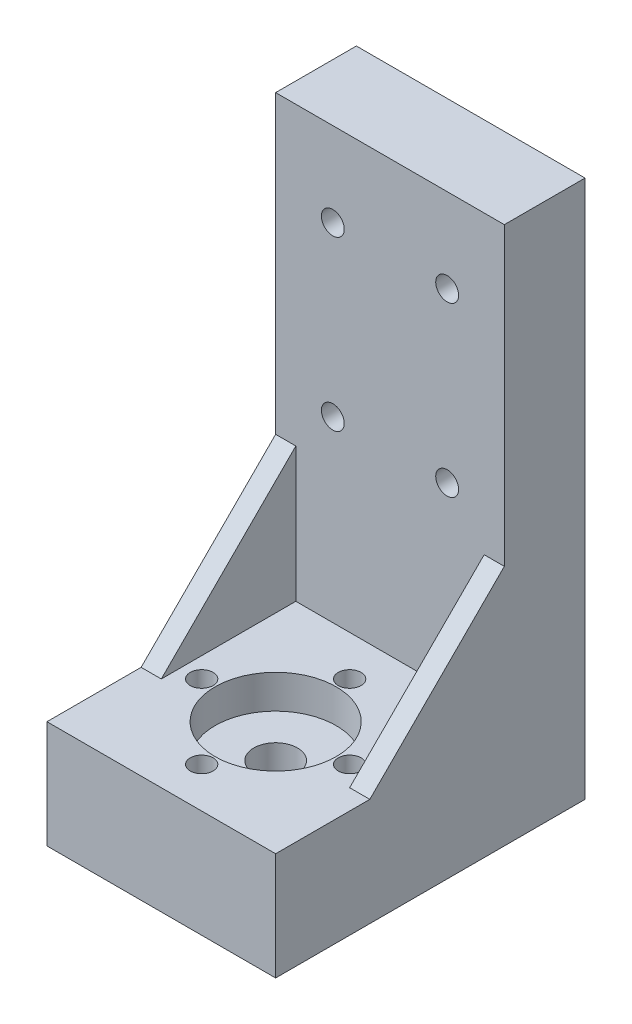
SolidWorks part; units mm, degrees
material "ABS"
ref_plane "Front Plane" through (0, 0, 0) normal (0, 0, 1) x (1, 0, 0)
ref_plane "Top Plane" through (0, 0, 0) normal (0, 1, 0) x (1, 0, 0)
ref_plane "Right Plane" through (0, 0, 0) normal (1, 0, 0) x (0, 0, -1)
sketch "Sketch1" plane through (0, 0, 0) normal (0, 1, 0) x (1, 0, 0)
  line L1 (17, -17) -> (-17, -17)
  line L2 (17, -17) -> (17, 17)
  line L3 (17, 17) -> (-17, 17)
  line L4 (-17, -17) -> (-17, 17)
  line L5 (17, -17) -> (-17, 17) construction
  line L6 (17, 17) -> (-17, -17) construction
  point P0 (0, 0)
  dimension "D1" = 34
  dimension "D2" = 34
extrude "Boss-Extrude1" add sketch "Sketch1" along normal blind 16
sketch "Sketch2" plane through (0, 0, -17) normal (0, 0, -1) x (-1, 0, 0)
  line L1 (-17, 0) -> (17, 0)
  line L2 (-17, 0) -> (-17, 80)
  line L3 (-17, 80) -> (17, 80)
  line L4 (17, 0) -> (17, 80)
  dimension "D1" = 34
  dimension "D2" = 80
extrude "Boss-Extrude2" add sketch "Sketch2" along normal blind 12
sketch "Sketch3" plane through (0, 16, 0) normal (0, 1, 0) x (1, 0, 0)
  line L2 (-17, 17) -> (-17, -17) construction
  line L3 (17, 17) -> (-17, 17) construction
  circle A0 centre (0, 0) radius 3.25
  circle A1 centre (0, 11) radius 1.7
  circle A2 centre (11, 0) radius 1.7
  circle A3 centre (0, -11) radius 1.7
  circle A4 centre (-11, 0) radius 1.7
  point P16 (0, 0)
  dimension "D1" = 6.5
  dimension "D2" = 3.4
  dimension "D3" = 11
  dimension "D4" = 17
  dimension "D6" = 11
  dimension "D7" = 17
  dimension "D5" = 4
extrude "Cut-Extrude2" cut sketch "Sketch3" against normal through all
sketch "Sketch4" plane through (0, 16, 0) normal (0, 1, 0) x (1, 0, 0)
  circle A0 centre (0, 0) radius 9
  dimension "D1" = 18
extrude "Cut-Extrude3" cut sketch "Sketch4" against normal blind 5
sketch "Sketch5" plane through (0, 0, -17) normal (0, 0, 1) x (1, 0, 0)
  line L0 (-17, 16) -> (-17, 80) construction
  line L1 (17, 80) -> (17, 16) construction
  line L2 (-17, 80) -> (17, 80) construction
  circle A0 centre (-8.5, 67.5) radius 1.7
  circle A1 centre (8.5, 67.5) radius 1.7
  circle A2 centre (8.5, 42.5) radius 1.7
  circle A3 centre (-8.5, 42.5) radius 1.7
  dimension "D1" = 3.4
  dimension "D2" = 8.5
  dimension "D3" = 8.5
  dimension "D4" = 12.5
  dimension "D5" = 37.5
extrude "Cut-Extrude4" cut sketch "Sketch5" against normal through all
sketch "Sketch6" plane through (17, 0, 0) normal (1, 0, 0) x (0, 0, -1)
  line L0 (17, 16) -> (-3, 16)
  line L1 (-17, 16) -> (17, 16) construction
  line L2 (17, 16) -> (17, 36)
  line L3 (17, 80) -> (17, 16) construction
  line L4 (17, 36) -> (-3, 16)
  dimension "D1" = 20
  dimension "D2" = 20
extrude "Boss-Extrude3" add sketch "Sketch6" against normal blind 3
sketch "Sketch7" plane through (-17, 0, 0) normal (-1, 0, 0) x (0, 0, 1)
  line L0 (-17, 16) -> (-17, 36)
  line L1 (-17, 16) -> (-17, 80) construction
  line L2 (-17, 16) -> (-17, 36) construction
  line L3 (-17, 16) -> (3, 16)
  line L6 (3, 16) -> (-17, 36)
  line L7 (-17, 36) -> (3, 16) construction
  dimension "D1" = 20
extrude "Boss-Extrude4" add sketch "Sketch7" against normal blind 3
equation "\"Feature 1 Length\"= 34mm"
equation "\"Mount Width\"= 34mm"
equation "\"Feature 1 thickness\"= 16mm"
equation "\"feature 2 height\"= 80mm"
equation "\"Feature 2 thickness\"= 12mm"
equation "\"D2@Sketch1\"=\"Feature 1 Length\""
equation "\"D1@Sketch1\"=\"Mount Width\""
equation "\"D1@Boss-Extrude1\"=\"Feature 1 thickness\""
equation "\"D2@Sketch2\"=\"feature 2 height\""
equation "\"D1@Sketch2\"=\"Mount Width\""
equation "\"D1@Boss-Extrude2\"=\"Feature 2 thickness\""
equation "\"Gusset thickness\"= 3mm"
equation "\"D1@Boss-Extrude3\"=\"Gusset thickness\""
